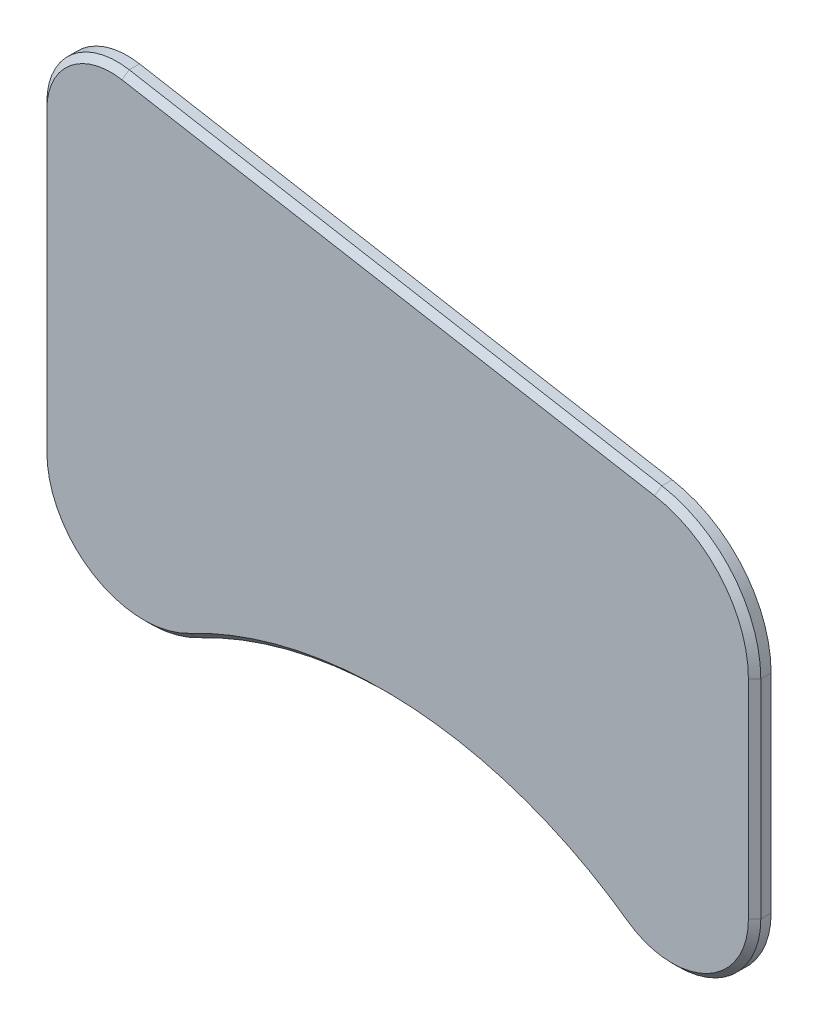
SolidWorks part; units mm, degrees
ref_plane "Front Plane" through (0, 0, 0) normal (0, 0, 1) x (1, 0, 0)
ref_plane "Top Plane" through (0, 0, 0) normal (0, 1, 0) x (1, 0, 0)
ref_plane "Right Plane" through (0, 0, 0) normal (1, 0, 0) x (0, 0, -1)
sketch "Sketch1" plane through (0, 0, 0) normal (0, 0, 1) x (1, 0, 0)
  line L0 (-48.9642, 39.0811) -> (59.0358, 20.0378) construction
  line L1 (83, -8.5217) -> (83, -33.5217) construction
  line L2 (-70.048, 42.7987) -> (59.0358, 20.0378)
  line L3 (83, -8.5217) -> (83, -58.9217)
  line L13 (-68, -36.5217) -> (-80, -36.5217) construction
  line L14 (-90, -33.5217) -> (-90, 10.5217)
  line L15 (-90, -45.9217) -> (-90, 26.057)
  line L16 (63, -78.9217) -> (-69.3957, -78.9217) construction
  arc A0 (83, -8.5217) -> (59.0358, 20.0378) centre (54, -8.5217) ccw construction
  arc A1 (83, -8.5217) -> (59.0358, 20.0378) centre (54, -8.5217) ccw
  arc A6 (-90, 26.057) -> (-70.048, 42.7987) centre (-73, 26.057) cw
  arc A7 (-90, -45.9217) -> (-53.3579, -68.0454) centre (-65, -45.9217) ccw
  arc A8 (83, -58.9217) -> (51.3684, -75.1915) centre (63, -58.9217) cw
  arc A9 (51.3684, -75.1915) -> (-53.3579, -68.0454) centre (-6.7894, -156.5405) ccw
  point P16 (-65, -70.9217)
  dimension "D2" = 17
  dimension "D3" = 20
  dimension "D4" = 25
  dimension "D5" = 100
  dimension "D6" = 34.4
  dimension "D7" = 8
  dimension "D1" = 7
extrude "Boss-Extrude1" add sketch "Sketch1" along normal blind 4
chamfer "Chamfer1" distance 1.5 angle 45 8 edges at (72.1479, -76.7069, 4) (83, -33.7217, 4) (0.0183, -56.7725, 4) (76.2153, 10.1192, 4) (-77.9218, -67.3232, 4) (-5.5061, 31.4182, 4) (-90, -9.9323, 4) (-83.9274, 39.0797, 4)
